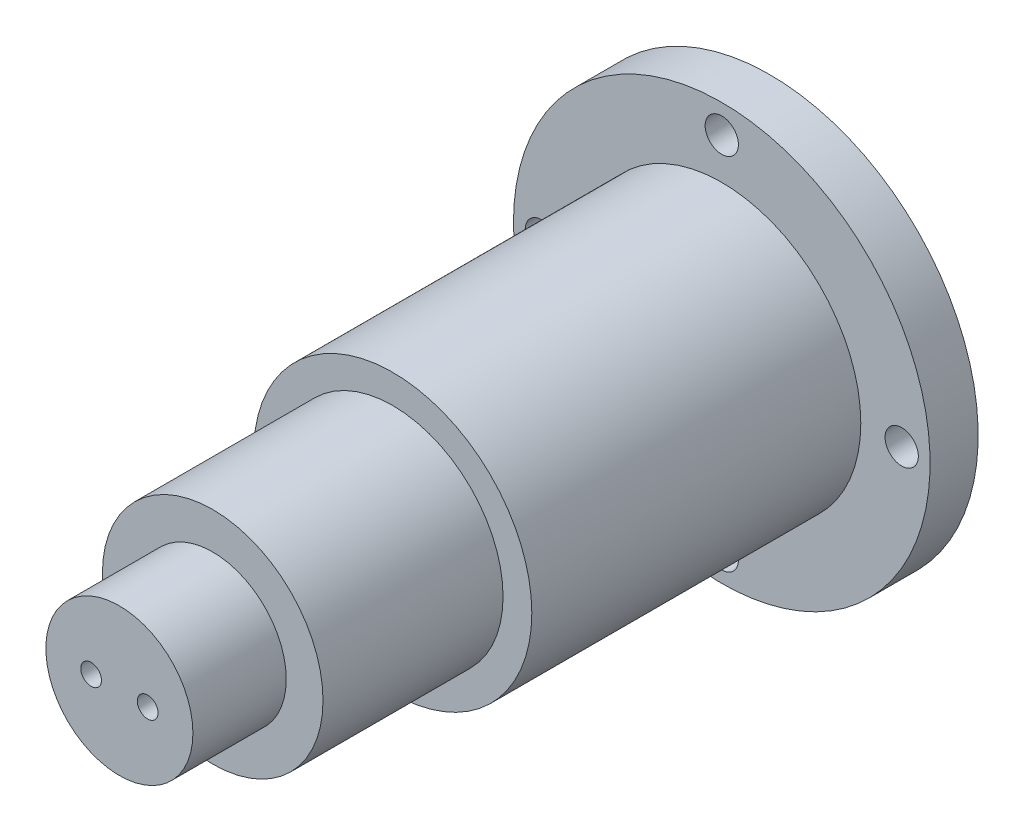
SolidWorks part; units mm, degrees
ref_plane "Front Plane" through (0, 0, 0) normal (0, 0, 1) x (1, 0, 0)
ref_plane "Top Plane" through (0, 0, 0) normal (0, 1, 0) x (1, 0, 0)
ref_plane "Right Plane" through (0, 0, 0) normal (1, 0, 0) x (0, 0, -1)
ref_plane "Plane1" through (0, 0, 0) normal (0, -1, 0) x (1, 0, 0)
sketch "Sketch1" plane through (0, 0, 0) normal (0, -1, 0) x (1, 0, 0)
  line L0 (22.1, 5.1) -> (0, 5.1)
  line L1 (0, 5.1) -> (0, 0)
  line L2 (0, 0) -> (22.1, 0)
  line L3 (22.1, 0) -> (22.1, 5.1)
  line L4 (0, 5.1) -> (0, 0) construction
revolve "Revolve1" add sketch "Sketch1" angle 360 about L4
sketch "Sketch2" plane through (0, 0, 5.1) normal (0, 0, 1) x (1, 0, 0)
  circle A0 centre (0, 0) radius 14.75
extrude "Boss-Extrude1" add sketch "Sketch2" along normal blind 34.9
sketch "Sketch3" plane through (0, 0, 40) normal (0, 0, 1) x (1, 0, 0)
  circle A0 centre (0, 0) radius 11.7
extrude "Boss-Extrude2" add sketch "Sketch3" along normal blind 19.1
sketch "Sketch4" plane through (0, 0, 59.1) normal (0, 0, 1) x (1, 0, 0)
  circle A0 centre (0, 0) radius 7.8
extrude "Boss-Extrude3" add sketch "Sketch4" along normal blind 9.9
hole_wizard "M10 Clearance Hole1" positions "Sketch6" profile "Sketch5" hole size "M10" standard "ANSI Metric"
sketch "Sketch6" plane through (0, 0, 0) normal (0, 0, -1) x (-1, 0, 0)
  point P0 (0, 0)
sketch "Sketch5" plane through (0, 0, 0) normal (1, 0, 0) x (0, 1, 0)
  line L0 (0, 0) -> (0, 22.6255)
  line L1 (0, 22.6255) -> (6.35, 18.81)
  line L2 (6.35, 18.81) -> (6.35, 0)
  line L5 (6.35, 0) -> (0, 0)
  line L10 (0, 22.6255) -> (-6.35, 18.81) construction
  line L11 (0, -6.35) -> (0, 107.95) construction
  dimension "Hole Dia." = 12.7
  dimension "Hole Depth" = 18.81
  dimension "Drill Angle" = 118
hole_wizard "Ø2.2 (2.2) Diameter Hole1" positions "Sketch8" profile "Sketch7" hole size "Ø2.2" standard "ANSI Metric"
sketch "Sketch8" plane through (0, 0, 69) normal (0, 0, 1) x (1, 0, 0)
  point P0 (-3, 0)
  point P1 (3, 0)
sketch "Sketch7" plane through (-3, 0, 69) normal (1, 0, 0) x (0, -1, 0)
  line L0 (0, 0) -> (0, 15)
  line L1 (0, 15) -> (1.1, 15)
  line L2 (1.1, 15) -> (1.1, 0)
  line L5 (1.1, 0) -> (0, 0)
  line L10 (0, 15) -> (-1.1, 15) construction
  line L11 (0, -6.35) -> (0, 107.95) construction
  dimension "Hole Dia." = 2.2
  dimension "Hole Depth" = 15
  dimension "Drill Angle" = 180
hole_wizard "M3 Clearance Hole1" positions "Sketch10" profile "Sketch9" hole size "M3" standard "ANSI Metric"
sketch "Sketch10" plane through (0, 0, 0) normal (0, 0, -1) x (-1, 0, 0)
  point P0 (0, 19.0875)
  point P1 (-19.0875, 0)
  point P2 (0, -19.0875)
  point P3 (19.0875, 0)
sketch "Sketch9" plane through (0, 19.0875, 0) normal (1, 0, 0) x (0, 1, 0)
  line L0 (0, 0) -> (0, 69)
  line L1 (0, 69) -> (1.765, 69)
  line L2 (1.765, 69) -> (1.765, 0)
  line L5 (1.765, 0) -> (0, 0)
  line L11 (0, -6.35) -> (0, 107.95) construction
  dimension "Thru Hole Dia." = 3.53
  dimension "Thru Hole Depth" = 69
chamfer "Chamfer1" distance 2 angle 45 1 edges at (-6.35, 0, 0)
